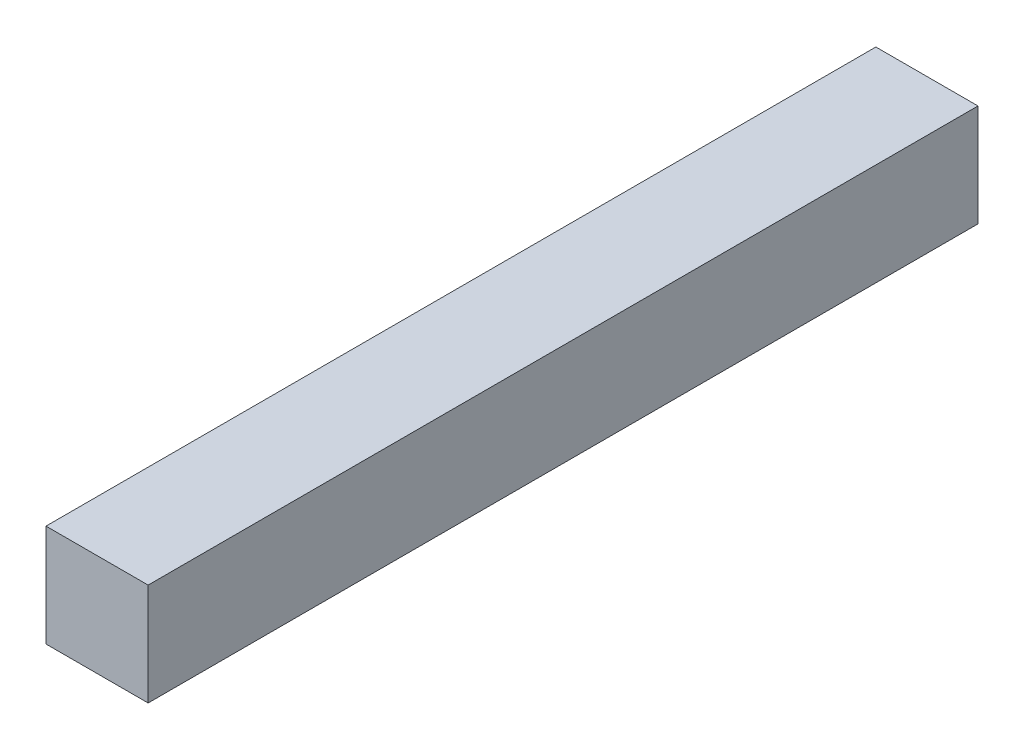
SolidWorks part; units mm, degrees
ref_plane "Plano frontal" through (0, 0, 0) normal (0, 0, 1) x (1, 0, 0)
ref_plane "Plano superior" through (0, 0, 0) normal (0, 1, 0) x (1, 0, 0)
ref_plane "Plano direito" through (0, 0, 0) normal (1, 0, 0) x (0, 0, -1)
sketch "Esboço1" plane through (0, 0, 0) normal (0, 0, 1) x (1, 0, 0)
  line L1 (0, 0) -> (8, 0)
  line L2 (0, 0) -> (0, 8)
  line L3 (0, 8) -> (8, 8)
  line L4 (8, 0) -> (8, 8)
extrude "Ressalto-extrusão1" add sketch "Esboço1" along normal blind 65
